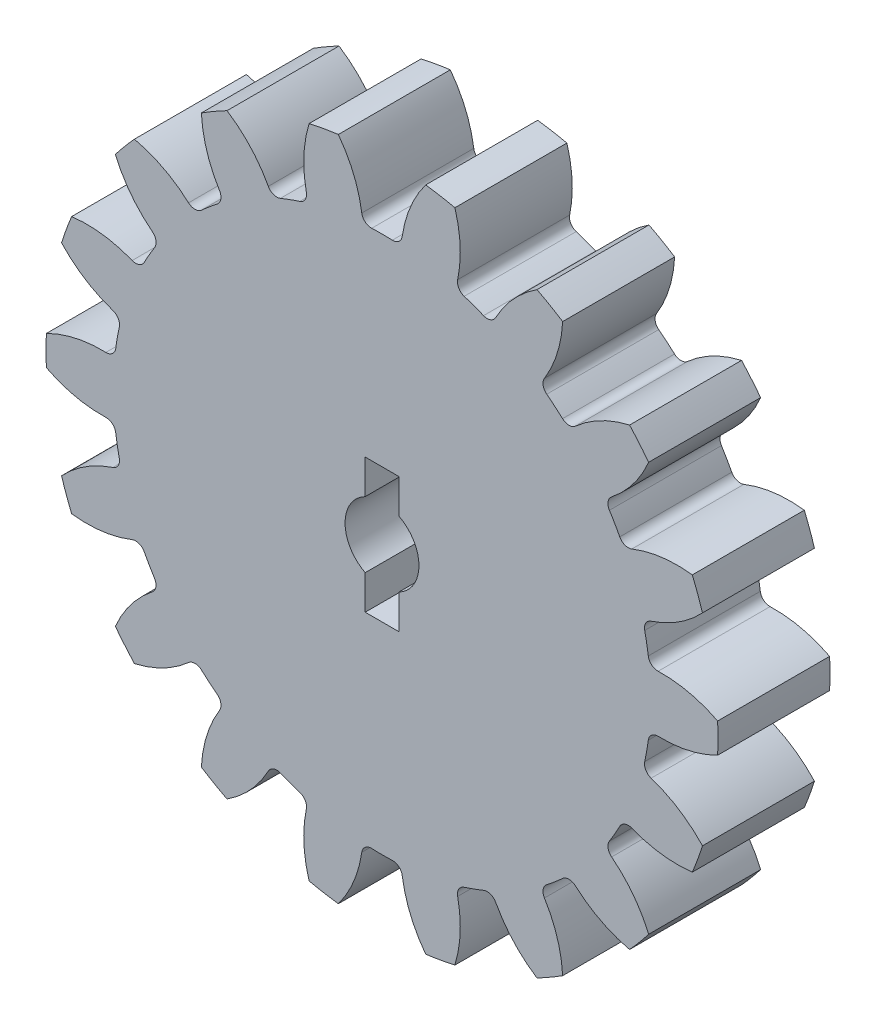
SolidWorks part; units mm, degrees
ref_plane "Front" through (0, 0, 0) normal (0, 0, 1) x (1, 0, 0)
ref_plane "Top" through (0, 0, 0) normal (0, 1, 0) x (1, 0, 0)
ref_plane "Right" through (0, 0, 0) normal (1, 0, 0) x (0, 0, -1)
sketch "Sketch1" plane through (0, 0, 0) normal (0, 0, 1) x (1, 0, 0)
  circle A0 centre (0, 0) radius 12
  circle A1 centre (0, 0) radius 15
  circle A2 centre (0, 0) radius 13.5
  dimension "D1" = 30
  dimension "D2" = 24
  dimension "D3" = 27
extrude "Boss-Extrude1" add sketch "Sketch1" along normal mid plane 5 contours A1
sketch "Sketch3" plane through (0, 0, 0) normal (0, 0, 1) x (1, 0, 0)
  line L0 (0, 0) -> (0, 15) construction
  line L1 (0, 0) -> (-0.8606, 11.9691) construction
  line L2 (-1.1766, 13.4486) -> (1.1766, 13.4486) construction
  line L3 (-1.7058, 14.9027) -> (0, 10.2159) construction
  line L4 (1.1766, 13.4486) -> (3.4941, 13.04) construction
  line L5 (2.6047, 14.7721) -> (0, 0) construction
  arc A0 (-0.8606, 11.9691) -> (0.8606, 11.9691) centre (0, 0) cw
  arc A4 (1.9502, 14.8727) -> (-1.9502, 14.8727) centre (0, 0) ccw
  circle A5 centre (0, 0) radius 15 construction
  arc A7 (-1.9502, 14.8727) -> (-0.8606, 11.9691) centre (-6.3201, 11.5766) cw
  arc A10 (1.9502, 14.8727) -> (0.8606, 11.9691) centre (6.3201, 11.5766) ccw
  circle A11 centre (0, 0) radius 12 construction
  circle A12 centre (0, 0) radius 13.5 construction
  dimension "D1" = 20
  dimension "D2" = 10
extrude "Cut-Extrude1" cut sketch "Sketch3" against normal through all both and the other way through all contours A10 A4 A7 A0
fillet "Fillet2" radius 0.43 2 edges at (-0.8606, 11.9691, 0) (0.8606, 11.9691, 0)
pattern_circular "CirPattern1" count 18 over 360 about axis through (0, 0, 0) along (0, 0, 1) of "Cut-Extrude1", "Fillet2"
sketch "Sketch4" plane through (0, 0, 0) normal (0, 0, 1) x (1, 0, 0)
  line L0 (-0.75, 3) -> (0.75, 3)
  line L1 (-0.75, -3) -> (0.75, -3) construction
  line L3 (-0.75, 3) -> (0.75, 3) construction
  line L7 (0.75, 3) -> (0.75, 1.4697)
  line L8 (-0.75, 3) -> (-0.75, 1.4697)
  line L9 (-0.75, -1.4697) -> (-0.75, -3)
  line L10 (-0.75, -3) -> (0.75, -3)
  line L11 (0.75, -3) -> (0.75, -1.4697)
  arc A1 (-0.75, 1.4697) -> (-0.75, -1.4697) centre (0, 0) ccw
  arc A2 (0.75, 1.4697) -> (0.75, -1.4697) centre (0, 0) cw
  dimension "D1" = 1.65
  dimension "D4" = 1.65
  dimension "D2" = 6
  dimension "D3" = 1.5
  dimension "D5" = 1.5
  dimension "D6" = 1.5303
extrude "Through_Center_Hole" cut sketch "Sketch4" against normal through all both and the other way through all
sketch "Sketch5" plane through (0, 0, 2.5) normal (0, 0, 1) x (1, 0, 0)
  circle A0 centre (0, 0) radius 1.6476
  dimension "D1" = 3.2952
equation "\"od\"= 30'outside diameter"
equation "\"n\"= 18'number of teeth"
equation "\"m\"= \"od\" / ( \"n\" + 2 )'module"
equation "\"p\"= \"m\" * pi'pitch"
equation "\"d\"= \"m\" * \"n\"'primitive diameter"
equation "\"da\"= \"d\" + 2 * \"m\"'head diamater"
equation "\"df\"= \"d\" - 2 * \"m\"'foot diameter"
equation "\"D1@Sketch1\"=\"od\""
equation "\"D2@Sketch1\"=\"df\""
equation "\"D3@Sketch1\"=\"d\""
equation "\"D2@Sketch3\"=180/\"n\""
equation "\"D1@CirPattern1\"=\"n\""
